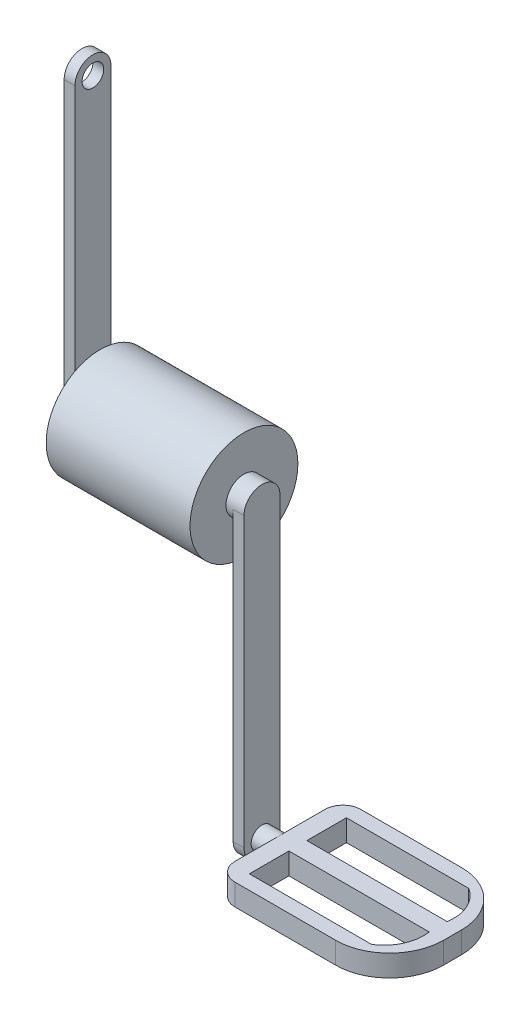
SolidWorks part; units mm, degrees
other "Pedal"
other "Pedal_Rad"
ref_plane "Front Plane" through (0, 0, 0) normal (0, 0, 1) x (1, 0, 0)
ref_plane "Top Plane" through (0, 0, 0) normal (0, 1, 0) x (1, 0, 0)
ref_plane "Right Plane" through (0, 0, 0) normal (1, 0, 0) x (0, 0, -1)
sketch "Sketch1" plane through (0, 0, 0) normal (1, 0, 0) x (0, 0, -1)
  circle A0 centre (0, 0) radius 15
  dimension "D1" = 30
extrude "Boss-Extrude1" add sketch "Sketch1" along normal mid plane 40
sketch "Sketch2" plane through (0, 0, 0) normal (1, 0, 0) x (0, 0, -1)
  circle A0 centre (0, 0) radius 5
  dimension "D1" = 10
extrude "Boss-Extrude2" add sketch "Sketch2" along normal mid plane 50
sketch "Sketch3" plane through (25, 0, 0) normal (1, 0, 0) x (0, 0, -1)
  line L1 (-5, 0) -> (5, 0)
  line L2 (-5, 0) -> (-5, -80)
  line L4 (5, 0) -> (5, -80)
  circle A0 centre (0, 0) radius 5 construction
  circle A1 centre (0, 0) radius 5 construction
  arc A2 (-5, -80) -> (5, -80) centre (0, -80) ccw
  circle A3 centre (0, -80) radius 3
  point P9 (5, -60.7282)
  dimension "D2" = 2
  dimension "D1" = 80
extrude "Boss-Extrude3" add sketch "Sketch3" against normal blind 3
sketch "Sketch4" plane through (-25, 0, 0) normal (-1, 0, 0) x (0, 0, 1)
  line L1 (-5, 0) -> (5, 0)
  line L2 (-5, 0) -> (-5, 80)
  line L4 (5, 0) -> (5, 80)
  circle A0 centre (0, 0) radius 5 construction
  circle A1 centre (0, 0) radius 5 construction
  arc A2 (5, 80) -> (-5, 80) centre (0, 80) ccw
  circle A3 centre (0, 80) radius 3
  circle A5 centre (0, -80) radius 3 construction
  arc A6 (-5, -80) -> (5, -80) centre (0, -80) ccw construction
  dimension "D1" = 80
extrude "Boss-Extrude4" add sketch "Sketch4" against normal blind 3
sketch "Sketch5" plane through (22, 0, 0) normal (-1, 0, 0) x (0, 0, 1)
  circle A0 centre (0, -80) radius 3 construction
  circle A1 centre (0, -80) radius 3
extrude "Boss-Extrude5" add sketch "Sketch5" against normal blind 8 separate body
sketch "Sketch6" plane through (30, 0, 0) normal (1, 0, 0) x (0, 0, -1)
  line L0 (-17.5, -80) -> (17.5, -80) construction
  line L1 (-17.5, -77) -> (17.5, -77)
  line L2 (-17.5, -77) -> (-17.5, -83)
  line L3 (-17.5, -83) -> (17.5, -83)
  line L4 (17.5, -77) -> (17.5, -83)
  circle A0 centre (0, -80) radius 3 construction
  circle A1 centre (0, -80) radius 3 construction
  circle A2 centre (0, -80) radius 3 construction
  point P11 (0, 0)
  point P12 (0, -80)
  dimension "D1" = 35
extrude "Boss-Extrude6" add sketch "Sketch6" along normal blind 48
fillet "Fillet1" radius 15 2 edges at (78, -80, 17.5) (78, -80, -17.5)
fillet "Fillet2" radius 5 2 edges at (30, -80, 17.5) (30, -80, -17.5)
sketch "Sketch7" plane through (0, -77, 0) normal (0, 1, 0) x (1, 0, 0)
  line L0 (74, 2.5) -> (35, 2.5)
  line L1 (74, -2.5) -> (35, -2.5)
  line L2 (35, -2.5) -> (35, -13.5)
  line L3 (35, -13.5) -> (69, -13.5)
  line L5 (35, 2.5) -> (35, 13.5)
  line L6 (35, 13.5) -> (69, 13.5)
  line L8 (63, -17.5) -> (35, -17.5) construction
  line L9 (63, 17.5) -> (35, 17.5) construction
  line L10 (30, 0) -> (30, -12.5) construction
  line L11 (78, 2.5) -> (78, -2.5) construction
  arc A0 (74, 2.5) -> (69, 13.5) centre (63.1316, 4.1962) ccw
  arc A1 (69, -13.5) -> (74, -2.5) centre (63.1316, -4.1962) ccw
  dimension "D7" = 11
  dimension "D1" = 4
  dimension "D2" = 4
  dimension "D3" = 5
  dimension "D4" = 5
  dimension "D5" = 5
  dimension "D6" = 4
extrude "Cut-Extrude1" cut sketch "Sketch7" against normal blind 48
other "Save Bodies1"
